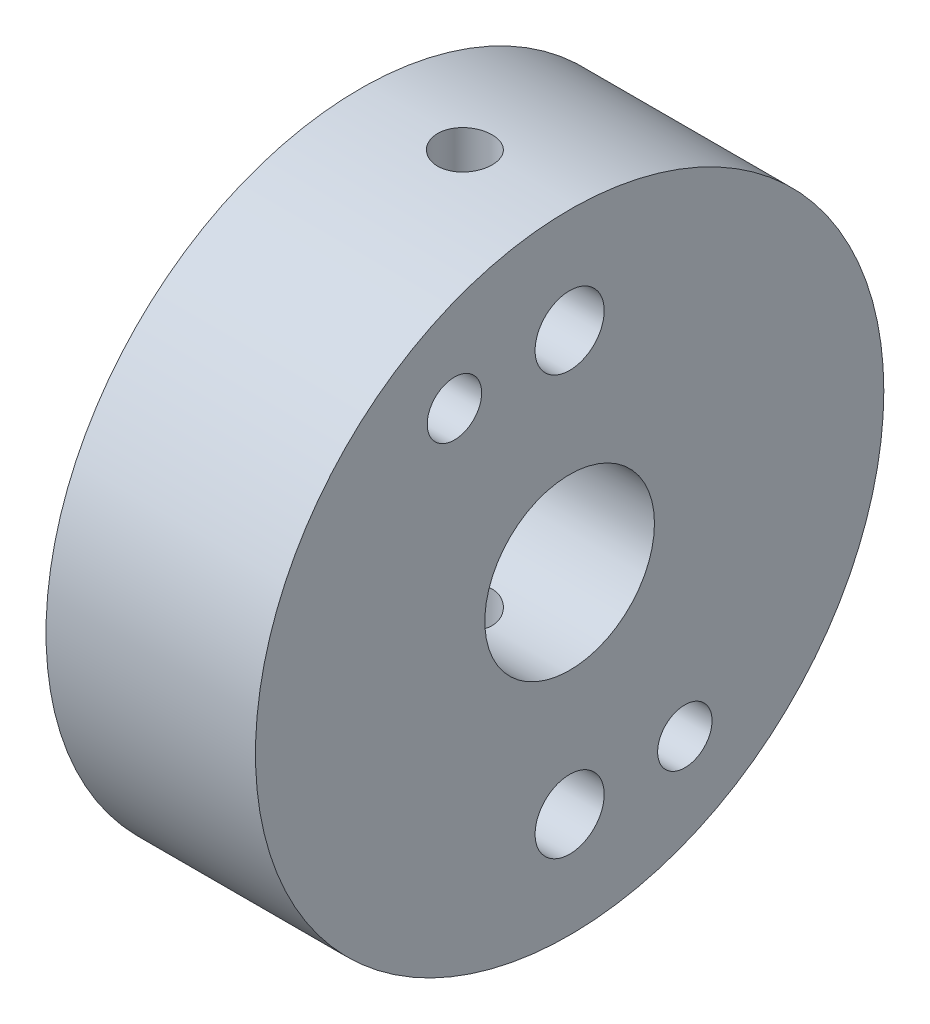
SolidWorks part; units mm, degrees
material "6063-O"
ref_plane "正面" through (0, 0, 0) normal (0, 0, 1) x (1, 0, 0)
ref_plane "平面" through (0, 0, 0) normal (0, 1, 0) x (1, 0, 0)
ref_plane "右側面" through (0, 0, 0) normal (1, 0, 0) x (0, 0, -1)
sketch "ｽｹｯﾁ1" plane through (0, 0, 0) normal (1, 0, 0) x (0, 0, -1)
  line L0 (0, 15) -> (0, -15) construction
  line L1 (-15, 0) -> (15, 0) construction
  circle A0 centre (0, 0) radius 15
  circle A1 centre (0, 0) radius 4.05
  dimension "D1" = 30
  dimension "D2" = 8.1
extrude "ﾎﾞｽ - 押し出し1" add sketch "ｽｹｯﾁ1" along normal blind 10
sketch "ｽｹｯﾁ2" plane through (0, 0, 0) normal (0, 1, 0) x (1, 0, 0)
  line L0 (0, 0) -> (10, 0) construction
  line L1 (0, 15) -> (0, -15) construction
  line L2 (10, -15) -> (10, 15) construction
  circle A0 centre (5, 0) radius 1.3
  dimension "D1" = 2.6
extrude "ｶｯﾄ - 押し出し1" cut sketch "ｽｹｯﾁ2" against normal through all both and the other way through all
sketch "ｽｹｯﾁ3" plane through (10, 0, 0) normal (1, 0, 0) x (0, 0, -1)
  line L0 (0, 0) -> (0, 50000) construction
  line L1 (0, 0) -> (50000, 0) construction
  line L2 (0, 0) -> (-5.5, 9.5263) construction
  line L3 (0, 0) -> (43301.2702, 25000) construction
  circle A0 centre (0, 10) radius 1.65
  circle A1 centre (0, -10) radius 1.65
  circle A2 centre (0, 10) radius 2 construction
  circle A3 centre (-5.5, 9.5263) radius 1.3
  circle A4 centre (5.5, -9.5263) radius 1.3
  dimension "D1" = 20
  dimension "D2" = 3.3
  dimension "D3" = 4
  dimension "D4" = 2.6
  dimension "D5" = 11
  dimension "D6" = 30
extrude "ｶｯﾄ - 押し出し2" cut sketch "ｽｹｯﾁ3" against normal through all
